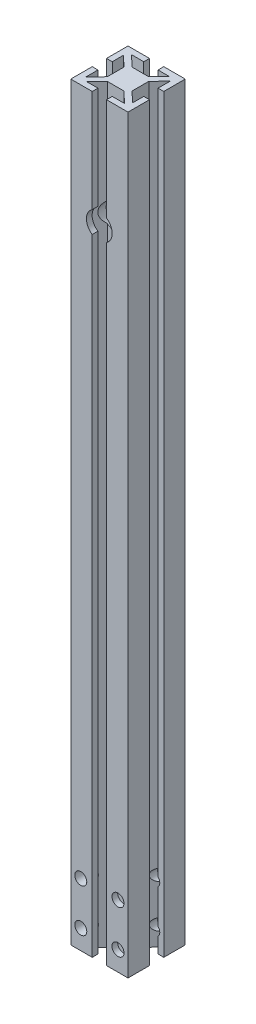
SolidWorks part; units mm, degrees
material "1060 Alloy"
ref_plane "Front Plane" through (0, 0, 0) normal (0, 0, 1) x (1, 0, 0)
ref_plane "Top Plane" through (0, 0, 0) normal (0, 1, 0) x (1, 0, 0)
ref_plane "Right Plane" through (0, 0, 0) normal (1, 0, 0) x (0, 0, -1)
sketch "Sketch1" plane through (0, 0, 0) normal (0, 1, 0) x (1, 0, 0)
  line L1 (-10, 10) -> (10, 10) construction
  line L2 (-10, 10) -> (-10, -10) construction
  line L3 (-10, -10) -> (10, -10) construction
  line L4 (10, 10) -> (10, -10) construction
  line L5 (-10, 10) -> (10, -10) construction
  line L6 (-10, -10) -> (10, 10) construction
  circle A0 centre (0, 0) radius 2
  point P0 (0, 0)
  dimension "D3" = 4
  dimension "D1" = 20
  dimension "D2" = 20
sketch "Sketch2" plane through (0, 0, 0) normal (0, 1, 0) x (1, 0, 0)
  line L0 (-10, 2.5) -> (-10, -2.5) construction
  line L1 (-10, 10) -> (-10, -10) construction
  line L2 (-10, -10) -> (-10, -2.5)
  line L3 (-10, -2.5) -> (-8, -2.5)
  line L4 (-8, -2.5) -> (-8, -6.7683)
  line L5 (-8, -6.7683) -> (-4.3583, -2.9445)
  line L6 (-4.3583, -2.9445) -> (-2.91, -4.3238)
  line L7 (-2.91, -4.3238) -> (-6.4243, -8)
  line L8 (-6.4243, -8) -> (-2.5, -8)
  line L9 (-2.5, -8) -> (-2.5, -10)
  line L10 (-10, -10) -> (10, -10) construction
  line L11 (-2.5, -10) -> (-10, -10)
  line L12 (-2.5, -10) -> (2.5, -10) construction
  line L14 (-10, -10) -> (10, 10) construction
  line L15 (-10, 2.5) -> (-10, 10)
  line L16 (-10, 10) -> (-2.5, 10)
  line L17 (-2.5, 10) -> (-2.5, 8)
  line L18 (-2.5, 8) -> (-6.7683, 8)
  line L19 (-6.7683, 8) -> (-2.9445, 4.3583)
  line L20 (-2.9445, 4.3583) -> (-4.3238, 2.91)
  line L21 (-4.3238, 2.91) -> (-8, 6.4243)
  line L22 (-8, 6.4243) -> (-8, 2.5)
  line L23 (-8, 2.5) -> (-10, 2.5)
  line L24 (2.5, 10) -> (10, 10)
  line L25 (10, 10) -> (10, 2.5)
  line L26 (10, 2.5) -> (8, 2.5)
  line L27 (8, 2.5) -> (8, 6.7683)
  line L28 (8, 6.7683) -> (4.3583, 2.9445)
  line L29 (4.3583, 2.9445) -> (2.91, 4.3238)
  line L30 (2.91, 4.3238) -> (6.4243, 8)
  line L31 (6.4243, 8) -> (2.5, 8)
  line L32 (2.5, 8) -> (2.5, 10)
  line L33 (10, -2.5) -> (10, -10)
  line L34 (10, -10) -> (2.5, -10)
  line L35 (2.5, -10) -> (2.5, -8)
  line L36 (2.5, -8) -> (6.7683, -8)
  line L37 (6.7683, -8) -> (2.9445, -4.3583)
  line L38 (2.9445, -4.3583) -> (4.3238, -2.91)
  line L39 (4.3238, -2.91) -> (8, -6.4243)
  line L40 (8, -6.4243) -> (8, -2.5)
  line L41 (8, -2.5) -> (10, -2.5)
  line L42 (-10, 10) -> (10, -10) construction
  line L43 (-4.3238, 4.3238) -> (4.3238, 4.3238)
  line L44 (-4.3238, 4.3238) -> (-4.3238, -4.3238)
  line L45 (-4.3238, -4.3238) -> (4.3238, -4.3238)
  line L46 (4.3238, 4.3238) -> (4.3238, -4.3238)
  line L47 (-4.3238, 4.3238) -> (4.3238, -4.3238) construction
  line L48 (-4.3238, -4.3238) -> (4.3238, 4.3238) construction
  point P5 (-10, 0)
  point P11 (0, 0)
  point P14 (-3.6341, -3.6341)
  point P19 (0, -10)
  dimension "D1" = 5
  dimension "D2" = 5
  dimension "D3" = 2
  dimension "D4" = 2
  dimension "D5" = 2
  dimension "D6" = 2
  dimension "D7" = 9
  dimension "D8" = 4
extrude "Boss-Extrude1" add sketch "Sketch2" along normal blind 262 contours L45 L44 L6 L5 L4 L3 L2 L11 L9 L8 L7 | L46 L29 L43 L20 L44 L6 L45 L38 | L39 L46 L45 L38 L37 L36 L35 L34 L33 L41 L40 | L43 L46 L29 L28 L27 L26 L25 L24 L32 L31 L30 | L44 L43 L20 L19 L18 L17 L16 L15 L23 L22 L21 | L46 L38 L45 | L46 L43 L29
sketch "Sketch4" plane through (10, 0, 0) normal (1, 0, 0) x (0, 0, -1)
  line L0 (0.0337, 262) -> (0.0337, 210.6) construction
  line L1 (2.9773, 262) -> (-2.91, 262) construction
  line L2 (0.0337, 210.6) -> (0.0337, 197.6) construction
  line L3 (0.0337, 197.6) -> (0.0337, 177.6) construction
  circle A0 centre (0.0337, 210.6) radius 2
  circle A1 centre (0.0337, 197.6) radius 2
  circle A2 centre (0.0337, 177.6) radius 2
  dimension "D2" = 4
  dimension "D5" = 4
  dimension "D6" = 4
  dimension "D1" = 51.4
  dimension "D3" = 13
  dimension "D4" = 20
extrude "Cut-Extrude1" cut sketch "Sketch4" against normal blind 110 contours A1 | A2 | A0
sketch "Sketch5" plane through (0, 0, -10) normal (0, 0, -1) x (-1, 0, 0)
  line L0 (0.0337, 262) -> (0.0337, 222.49) construction
  line L1 (2.9773, 262) -> (-2.91, 262) construction
  circle A0 centre (0.0337, 222.49) radius 4.5
  dimension "D2" = 9
  dimension "D1" = 39.51
extrude "Cut-Extrude2" cut sketch "Sketch5" against normal blind 110 contours A0
sketch "Sketch7" plane through (0, 0, -10) normal (0, 0, -1) x (-1, 0, 0)
  line L0 (0, 0) -> (0, 28) construction
  line L1 (6.5, 21.8611) -> (-6.5, 21.8611) construction
  line L2 (6.5, 6.8611) -> (-6.5, 6.8611) construction
  line L3 (-6.5, 6.8611) -> (-6.5, 21.8611) construction
  line L4 (6.5, 21.8611) -> (6.5, 6.8611) construction
  line L5 (10, 262) -> (10, 0) construction
  circle A0 centre (6.5, 21.8611) radius 2.1
  circle A1 centre (6.5, 6.8611) radius 2.1
  circle A2 centre (-6.5, 21.8611) radius 2.1
  circle A3 centre (-6.5, 6.8611) radius 2.1
  point P6 (0, 21.8611)
  point P9 (0, 6.8611)
  dimension "D3" = 4.2
  dimension "D4" = 4.2
  dimension "D1" = 28
  dimension "D2" = 3.5
  dimension "D5" = 15
sketch "Sketch9" plane through (-10, 0, 0) normal (-1, 0, 0) x (0, 0, 1)
  line L0 (0, 0) -> (0, 28) construction
  line L1 (6.5, 6) -> (-6.5, 6) construction
  line L2 (-6.5, 6) -> (-6.5, 21) construction
  line L3 (-6.5, 21) -> (6.5, 21) construction
  line L4 (6.5, 21) -> (6.5, 6) construction
  line L5 (10, 262) -> (10, 0) construction
  line L6 (-10, 0) -> (10, 0) construction
  circle A0 centre (6.5, 6) radius 2.1
  circle A1 centre (6.5, 21) radius 2.1
  circle A2 centre (-6.5, 21) radius 2.1
  circle A3 centre (-6.5, 6) radius 2.1
  point P6 (0, 6)
  dimension "D2" = 4.2
  dimension "D1" = 28
  dimension "D3" = 15
  dimension "D4" = 3.5
  dimension "D5" = 6
extrude "Cut-Extrude5" cut sketch "Sketch7" against normal blind 50
sketch "Sketch10" plane through (0, 0, -10) normal (0, 0, -1) x (-1, 0, 0)
  line L0 (0.0337, 262) -> (0.0337, 222.49) construction
  line L1 (2.9773, 262) -> (-2.91, 262) construction
  line L2 (6.5, 21.8611) -> (6.5, 6.8611) construction
  line L3 (6.5, 6.8611) -> (6.5, 0) construction
  line L4 (10, 0) -> (-10, 0) construction
  line L5 (6.5, 21.8611) -> (-6.5, 21.8611) construction
  circle A0 centre (6.5, 21.8611) radius 2.1
  dimension "D1" = 4.2
  dimension "D2" = 15
  dimension "D3" = 6.8611
  dimension "D4" = 39.51
sketch "Sketch11" plane through (10, 0, 0) normal (1, 0, 0) x (0, 0, -1)
  line L0 (0.0337, 210.6) -> (6.1999, 210.6) construction
  line L1 (0.0337, 197.6) -> (6.1999, 197.6) construction
  line L2 (0.0337, 177.6) -> (6.1999, 177.6) construction
  line L3 (6.1999, 177.6) -> (6.1999, 197.6) construction
  line L4 (6.1999, 197.6) -> (6.1999, 211.0862) construction
  dimension "D1" = 13
  dimension "D2" = 20
